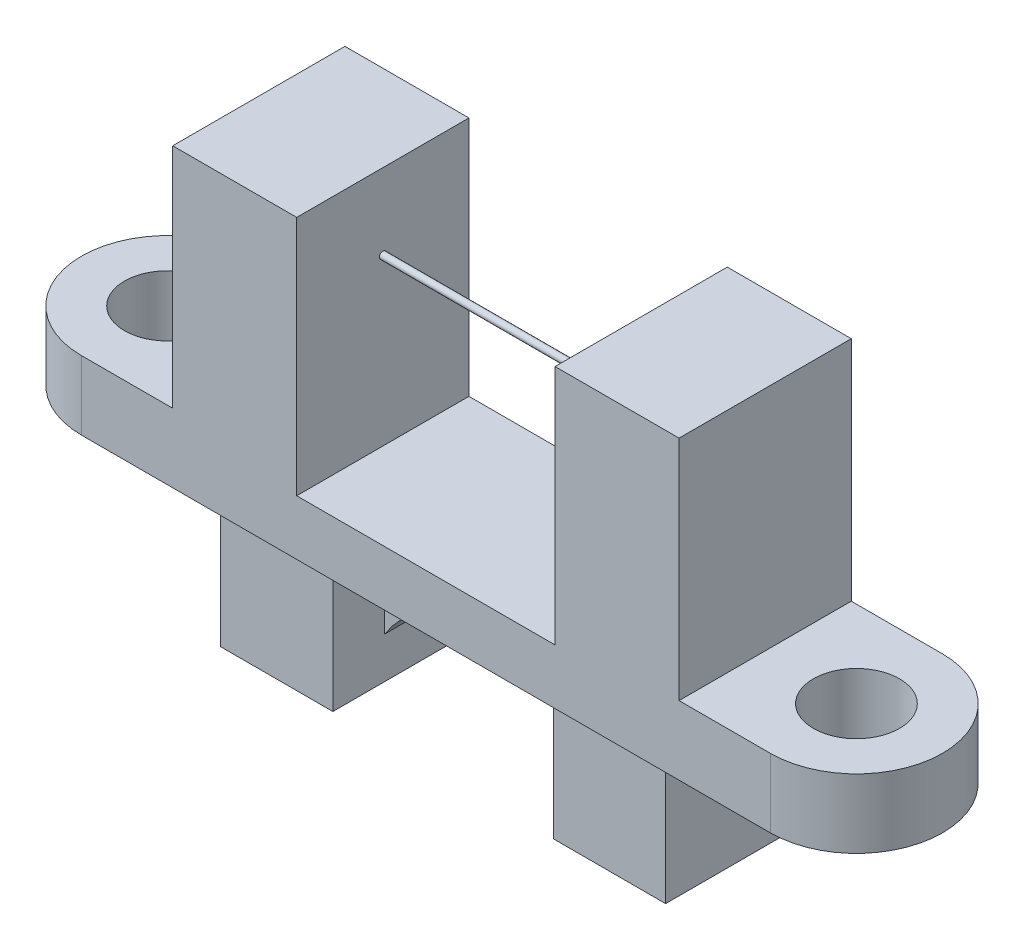
SolidWorks part; units mm, degrees
ref_plane "Front" through (0, 0, 0) normal (0, 0, 1) x (1, 0, 0)
ref_plane "Top" through (0, 0, 0) normal (0, 1, 0) x (1, 0, 0)
ref_plane "Right" through (0, 0, 0) normal (1, 0, 0) x (0, 0, -1)
sketch "Sketch1" plane through (0, 0, 0) normal (0, 1, 0) x (1, 0, 0)
  line L0 (0, 44.8439) -> (0, -42.4116) construction
  line L1 (-77.9827, 0) -> (80.4149, 0) construction
  line L2 (12.7, 3.175) -> (-12.7, 3.175)
  line L3 (12.7, -3.175) -> (-12.7, -3.175)
  arc A0 (12.7, -3.175) -> (12.7, 3.175) centre (12.7, 0) ccw
  arc A1 (-12.7, -3.175) -> (-12.7, 3.175) centre (-12.7, 0) cw
  point P10 (0, 3.175)
  point P13 (0, -3.175)
  dimension "D1" = 3.175
  dimension "D2" = 12.7
extrude "Base-Extrude" add sketch "Sketch1" along normal blind 2.54
sketch "Sketch2" plane through (0, 2.54, 0) normal (0, 1, 0) x (-1, 0, 0)
  line L0 (0, -9.1937) -> (0, 8.5411) construction
  line L1 (12.7, 3.175) -> (-12.7, 3.175) construction
  line L2 (4.7625, -3.175) -> (-4.7625, -3.175)
  line L3 (-12.7, -3.175) -> (12.7, -3.175) construction
  line L4 (4.7625, 3.175) -> (-4.7625, 3.175)
  line L5 (-4.7625, -3.175) -> (-4.7625, 3.175)
  line L6 (4.7625, -3.175) -> (4.7625, 3.175)
  point P12 (0, 3.175)
  point P13 (0, -3.175)
  dimension "D1" = 4.7625
extrude "Cut-Extrude1" cut sketch "Sketch2" against normal blind 0.508
sketch "Sketch3" plane through (0, 2.54, 0) normal (0, 1, 0) x (-1, 0, 0)
  line L0 (0, -9.6928) -> (0, 9.0786) construction
  line L1 (-4.7625, 3.175) -> (-12.7, 3.175) construction
  line L2 (-4.7625, -3.175) -> (-9.3345, -3.175)
  line L3 (-4.7625, -3.175) -> (-4.7625, 3.175)
  line L4 (-4.7625, 3.175) -> (-9.3345, 3.175)
  line L5 (-9.3345, -3.175) -> (-9.3345, 3.175)
  line L6 (9.3345, -3.175) -> (9.3345, 3.175)
  line L7 (4.7625, 3.175) -> (9.3345, 3.175)
  line L8 (4.7625, -3.175) -> (4.7625, 3.175)
  line L9 (4.7625, -3.175) -> (9.3345, -3.175)
  dimension "D1" = 9.3345
extrude "Boss-Extrude1" add sketch "Sketch3" along normal blind 8.382
sketch "Sketch4" plane through (0, 2.54, 0) normal (0, 1, 0) x (-1, 0, 0)
  line L0 (0, -9.675) -> (0, 9.903) construction
  circle A0 centre (-12.7, 0) radius 1.5875
  arc A1 (-12.7, 3.175) -> (-12.7, -3.175) centre (-12.7, 0) ccw construction
  circle A2 centre (12.7, 0) radius 1.5875
  dimension "D1" = 3.175
extrude "Cut-Extrude2" cut sketch "Sketch4" against normal through all
sketch "Sketch5" plane through (0, 0, 0) normal (0, -1, 0) x (1, 0, 0)
  line L0 (0, 11.5353) -> (0, -10.5757) construction
  line L1 (4.064, -2.54) -> (8.2042, -2.54)
  line L2 (-4.064, -2.54) -> (-8.2042, -2.54)
  line L3 (4.064, -2.54) -> (4.064, 2.54)
  line L4 (4.064, 2.54) -> (8.2042, 2.54)
  line L5 (8.2042, -2.54) -> (8.2042, 2.54)
  line L6 (-8.2042, -2.54) -> (-8.2042, 2.54)
  line L7 (-4.064, 2.54) -> (-8.2042, 2.54)
  line L8 (-4.064, -2.54) -> (-4.064, 2.54)
  line L11 (-16.9496, 0) -> (18.4146, 0) construction
  line L12 (11.74, 0) -> (-11.74, 0) construction
  point P8 (8.2042, 0)
  point P9 (4.064, 0)
  dimension "D1" = 2.54
  dimension "D2" = 8.2042
  dimension "D3" = 4.064
extrude "Boss-Extrude2" add sketch "Sketch5" along normal blind 4.826
sketch "Sketch6" plane through (0, 0, 0) normal (0, 0, 1) x (1, 0, 0)
  line L1 (-4.064, 0) -> (4.064, 0)
  line L2 (-4.064, 0) -> (-4.064, -3.3054)
  line L4 (4.064, 0) -> (4.064, -3.3054)
  arc A0 (-4.064, -3.3054) -> (4.064, -3.3054) centre (0, -5.9081) cw
extrude "Boss-Extrude3" add sketch "Sketch6" against normal mid plane 1.27
sketch "Sketch7" plane through (4.7625, 0, 0) normal (-1, 0, 0) x (0, 0, 1)
  line L0 (0, -11.74) -> (0, 11.74) construction
  line L1 (-3.175, 10.922) -> (3.175, 10.922) construction
  circle A0 centre (0, 8.128) radius 0.127
  dimension "D2" = 0.254
  dimension "D1" = 2.794
extrude "Boss-Extrude4" add sketch "Sketch7" along normal up to surface (9.525 mm away) up to face at (-4.7625, 6.477, 0)
sketch "Sketch8" plane through (0, -4.826, 0) normal (0, -1, 0) x (1, 0, 0)
  line L0 (0, -50) -> (0, 50) construction
  line L1 (11.74, 0) -> (-11.74, 0) construction
  circle A0 centre (-5.08, 0) radius 0.635
  circle A1 centre (-2.54, 0) radius 0.635
  circle A2 centre (0, 0) radius 0.635
  circle A3 centre (2.54, 0) radius 0.635
  circle A4 centre (5.08, 0) radius 0.635
  dimension "D3" = 1.27
  dimension "D2" = 10.16
  dimension "D1" = 5
extrude "Boss-Extrude5" [suppressed] add sketch "Sketch8" along normal blind 203.2
